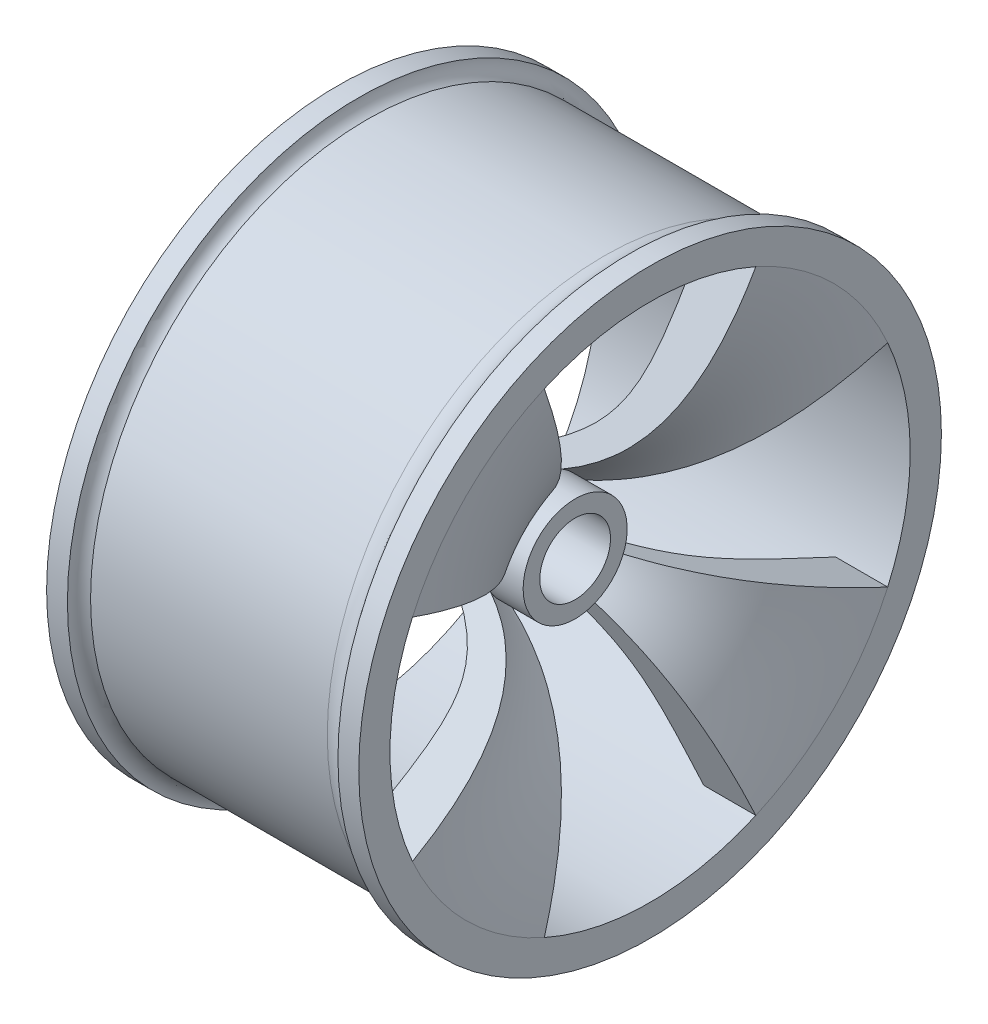
SolidWorks part; units mm, degrees
ref_plane "Front Plane" through (0, 0, 0) normal (0, 0, 1) x (1, 0, 0)
ref_plane "Top Plane" through (0, 0, 0) normal (0, 1, 0) x (1, 0, 0)
ref_plane "Right Plane" through (0, 0, 0) normal (1, 0, 0) x (0, 0, -1)
sketch "Sketch1" plane through (0, 0, 0) normal (0, 1, 0) x (1, 0, 0)
  line L0 (0, 0) -> (-6074.6801, 0) construction
  line L1 (0, 0) -> (0, 6074.6801) construction
  line L2 (-75, 125) -> (-75, 140)
  line L3 (-75, 140) -> (-65, 140)
  line L4 (-60.873, 133) -> (52.8756, 133)
  line L5 (65, 140) -> (75, 140)
  line L6 (75, 140) -> (75, 125)
  line L7 (50, 125) -> (-75, 125)
  line L8 (0, 17) -> (0, 25)
  arc A0 (-65, 140) -> (-60.873, 133) centre (-57, 140) ccw
  arc A1 (52.8756, 133) -> (65, 140) centre (52.8756, 147) ccw
  spline S0 degree 3 poles (75, 125) (69.6593, 66.9117) (47.9128, 31.2957) (0, 17) knots 0 0 0 0 1 1 1 1
  spline S1 degree 3 poles (0, 25) (43.41, 49.8107) (44.4434, 66.9319) (50, 125) knots 0 0 0 0 1 1 1 1
  point P17 (87.8756, 258)
  point P18 (87.8756, 258)
  point P19 (100, 265)
  point P20 (125, 125)
  point P22 (50, 125)
  dimension "D3" = 8
  dimension "D7" = 14
  dimension "D9" = 150
  dimension "D10" = 175
  dimension "D11" = 175
  dimension "D12" = 150
  dimension "D2" = 10
  dimension "D4" = 15
  dimension "D5" = 250
  dimension "D6" = 8
  dimension "D8" = 10
  dimension "D13" = 8
  dimension "D14" = 150
  dimension "D15" = 100
revolve "Revolve1" add sketch "Sketch1" angle 360 about L0
sketch "Sketch2" plane through (0, 0, 0) normal (-1, 0, 0) x (0, 0, 1)
  circle A0 centre (0, 0) radius 17 construction
  circle A1 centre (0, 0) radius 25
  circle A2 centre (0, 0) radius 25
  circle A3 centre (0, 0) radius 17
  dimension "D1" = 0
extrude "Boss-Extrude2" add sketch "Sketch2" along normal up to surface and the other way blind 39 up to face at (-75, 0, -125)
sketch "Sketch3" plane through (39, 0, 0) normal (1, 0, 0) x (0, 0, -1)
  line L0 (-12.5, 21.6506) -> (-50.8339, 114.1968)
  line L1 (12.5, 21.6506) -> (50.8339, 114.1968)
  line L2 (0, 0) -> (0, 50000) construction
  circle A0 centre (0, 0) radius 25 construction
  circle A1 centre (0, 0) radius 125 construction
  arc A3 (12.5, 21.6506) -> (-12.5, 21.6506) centre (0, 0) ccw
  arc A4 (50.8339, 114.1968) -> (-50.8339, 114.1968) centre (0, 0) ccw
  point P8 (-22.0483, 11.7844)
  point P9 (-14.6599, 20.2506)
  dimension "D1" = 22.5
  dimension "D2" = 25
extrude "Cut-Extrude1" cut sketch "Sketch3" along normal blind 644 and the other way blind 564
pattern_circular "CirPattern1" count 4 every 90 about axis through (0, 0, 0) along (1, 0, 0) of "Cut-Extrude1"
